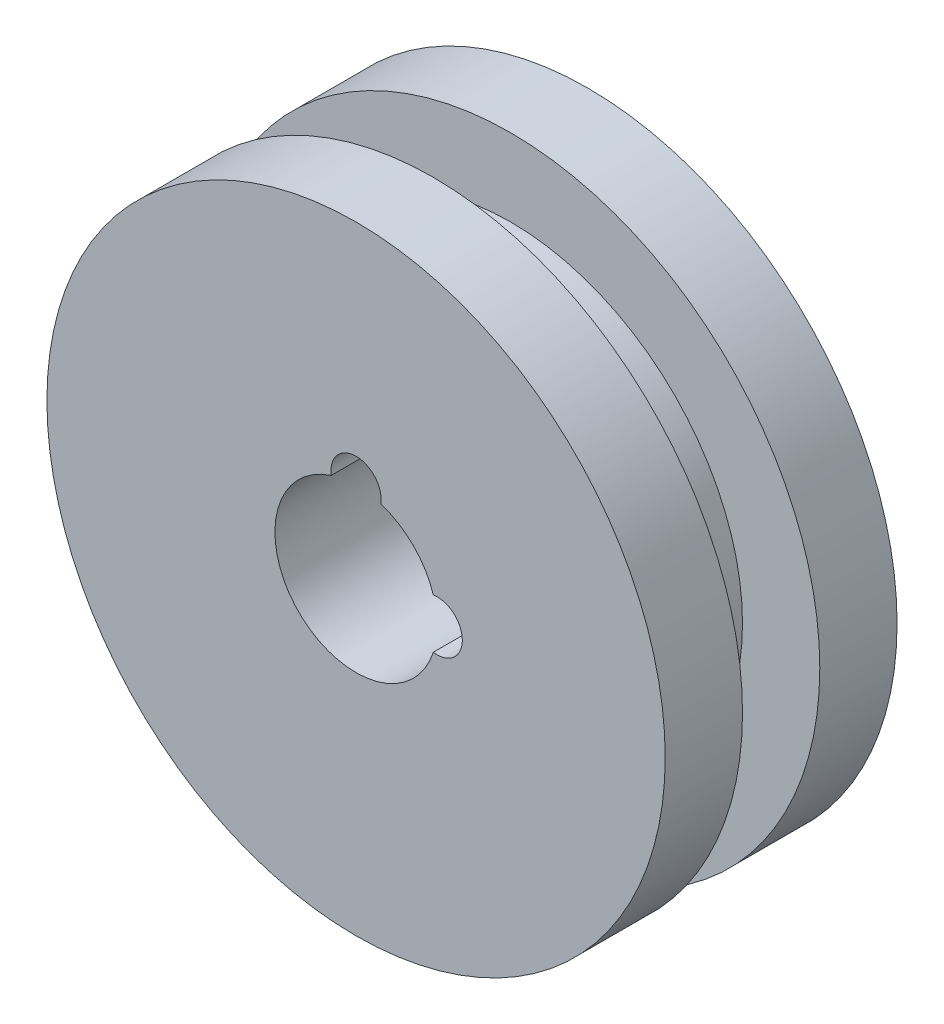
SolidWorks part; units mm, degrees
ref_plane "Plan de face" through (0, 0, 0) normal (0, 0, 1) x (1, 0, 0)
ref_plane "Plan de dessus" through (0, 0, 0) normal (0, 1, 0) x (1, 0, 0)
ref_plane "Plan de droite" through (0, 0, 0) normal (1, 0, 0) x (0, 0, -1)
sketch "Esquisse1" plane through (0, 0, 0) normal (0, 0, 1) x (1, 0, 0)
  arc A0 (-0.6422, 1.9994) -> (1.9994, -0.6422) centre (0, 0) ccw
  circle A1 centre (0, 0) radius 6
  arc A2 (1.9994, -0.6422) -> (1.9994, 0.6422) centre (2.1, 0) ccw
  arc A3 (0.6422, 1.9994) -> (-0.6422, 1.9994) centre (0, 2.1) ccw
  arc A4 (-0.6422, 1.9994) -> (0.6422, 1.9994) centre (0, 2.1) ccw construction
  arc A5 (0.6422, 1.9994) -> (-0.6422, 1.9994) centre (0, 0) ccw construction
  arc A6 (1.9994, 0.6422) -> (1.9994, -0.6422) centre (2.1, 0) ccw construction
  arc A7 (1.9994, -0.6422) -> (1.9994, 0.6422) centre (0, 0) ccw construction
  arc A8 (1.9994, 0.6422) -> (0.6422, 1.9994) centre (0, 0) ccw
  dimension "D1" = 12
  dimension "D2" = 4.2
  dimension "D3" = 1.3
  dimension "D4" = 1.3
extrude "Boss.-Extru.1" add sketch "Esquisse1" along normal mid plane 6
sketch "Esquisse2" plane through (0, 0, 3) normal (0, 0, 1) x (1, 0, 0)
  circle A0 centre (0, 0) radius 8
  circle A1 centre (0, 0) radius 6
  circle A2 centre (0, 0) radius 6 construction
  dimension "D1" = 16
extrude "Boss.-Extru.2" add sketch "Esquisse2" against normal blind 2
mirror "Symétrie1" about plane through (0, 0, 0) normal (0, 0, 1) of "Boss.-Extru.2"
